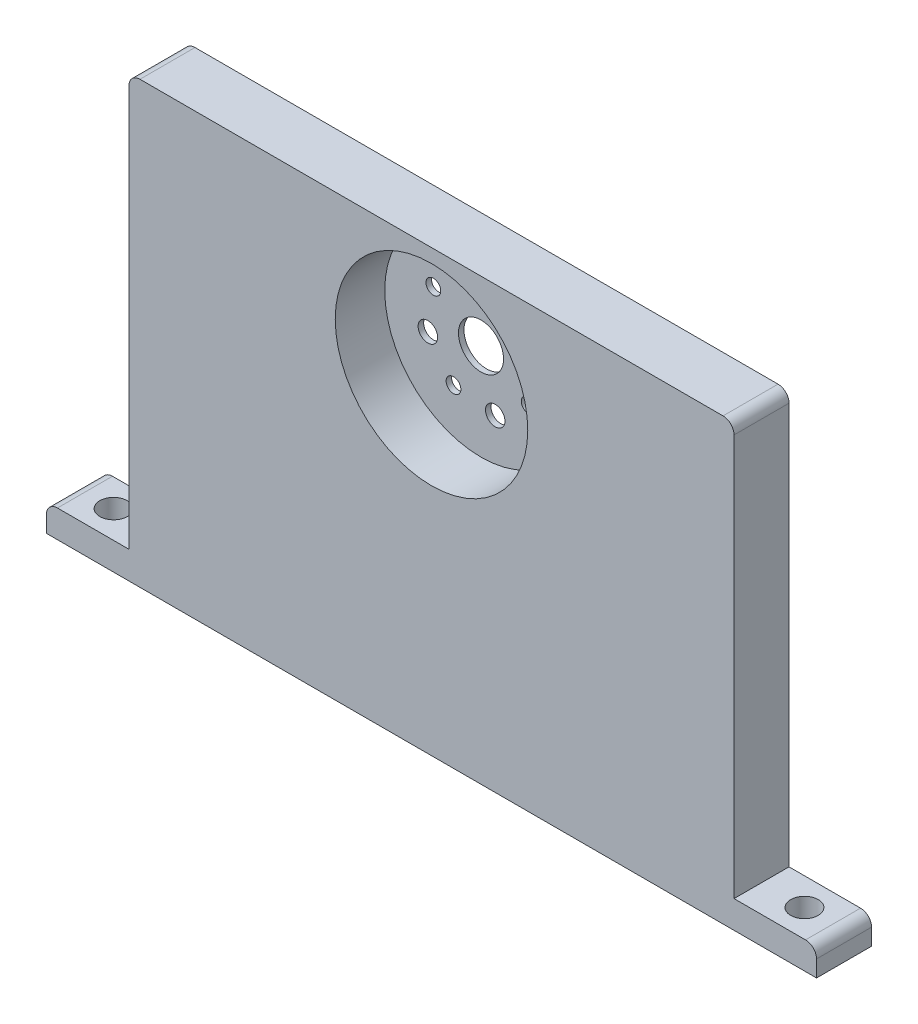
SolidWorks part; units mm, degrees
material "6061 Alloy"
ref_plane "Front Plane" through (0, 0, 0) normal (0, 0, 1) x (1, 0, 0)
ref_plane "Top Plane" through (0, 0, 0) normal (0, 1, 0) x (1, 0, 0)
ref_plane "Right Plane" through (0, 0, 0) normal (1, 0, 0) x (0, 0, -1)
sketch "Sketch1" plane through (0, 0, 0) normal (0, 1, 0) x (1, 0, 0)
  line L1 (0, 0) -> (139.7, 0)
  line L2 (0, 0) -> (0, 12.7)
  line L3 (0, 12.7) -> (139.7, 12.7)
  line L4 (139.7, 0) -> (139.7, 12.7)
  dimension "D1" = 12.7
  dimension "D2" = 139.7
extrude "Boss-Extrude1" add sketch "Sketch1" along normal blind 101.6
sketch "Sketch2" plane through (0, 0, 0) normal (-1, 0, 0) x (0, 0, 1)
  line L0 (-12.7, 101.6) -> (-12.7, 0) construction
  line L1 (0, 0) -> (-12.7, 0)
  line L2 (0, 0) -> (0, 6.35)
  line L3 (0, 6.35) -> (-12.7, 6.35)
  line L4 (-12.7, 0) -> (-12.7, 6.35)
  dimension "D1" = 6.35
extrude "Boss-Extrude2" add sketch "Sketch2" along normal blind 19.05
ref_plane "Plane1" through (69.85, 0, 0) normal (-1, 0, 0) x (0, 0, 1)
mirror "Mirror1" about plane through (69.85, 0, 0) normal (-1, 0, 0) of "Boss-Extrude2"
sketch "Sketch3" plane through (0, 0, 0) normal (0, 0, 1) x (1, 0, 0)
  line L0 (69.85, 101.6) -> (69.85, 0) construction
  line L1 (0, 101.6) -> (139.7, 101.6) construction
  line L2 (-19.05, 0) -> (158.75, 0) construction
  circle A0 centre (69.85, 76.2) radius 5.207
  dimension "D2" = 10.414
  dimension "D1" = 76.2
extrude "Cut-Extrude1" cut sketch "Sketch3" against normal up to next
sketch "Sketch4" plane through (0, 0, 0) normal (0, 0, 1) x (1, 0, 0)
  circle A0 centre (69.85, 76.2) radius 22.225
  dimension "D1" = 44.45
extrude "Cut-Extrude2" cut sketch "Sketch4" against normal blind 11.43
sketch "Sketch5" plane through (0, 0, -11.43) normal (0, 0, 1) x (1, 0, 0)
  line L0 (69.85, 76.2) -> (69.85, 88.9) construction
  line L1 (69.85, 76.2) -> (58.8515, 82.55) construction
  line L2 (69.85, 76.2) -> (66.563, 88.4673) construction
  line L3 (69.85, 76.2) -> (76.2, 87.1985) construction
  line L4 (69.85, 76.2) -> (82.1173, 79.487) construction
  line L5 (69.85, 76.2) -> (80.8485, 69.85) construction
  line L6 (69.85, 76.2) -> (73.137, 63.9327) construction
  line L7 (69.85, 76.2) -> (63.5, 65.2015) construction
  line L8 (69.85, 76.2) -> (57.5827, 72.913) construction
  circle A0 centre (69.85, 76.2) radius 12.7 construction
  circle A1 centre (58.8515, 82.55) radius 1.7018
  circle A2 centre (66.563, 88.4673) radius 2.2479
  circle A3 centre (82.1173, 79.487) radius 2.2479
  circle A4 centre (73.137, 63.9327) radius 2.2479
  circle A5 centre (57.5827, 72.913) radius 2.2479
  circle A6 centre (76.2, 87.1985) radius 1.7018
  circle A7 centre (80.8485, 69.85) radius 1.7018
  circle A8 centre (63.5, 65.2015) radius 1.7018
  point P6 (58.8515, 82.55)
  point P15 (69.85, 76.2)
  point P25 (69.85, 76.2)
  point P31 (69.85, 76.2)
  dimension "D1" = 25.4
  dimension "D4" = 3.4036
  dimension "D5" = 4.4958
  dimension "D2" = 60
  dimension "D3" = 8
  dimension "D6" = 4
  dimension "D7" = 4
extrude "Cut-Extrude3" cut sketch "Sketch5" against normal up to next
sketch "Sketch6" plane through (0, 6.35, 0) normal (0, 1, 0) x (1, 0, 0)
  line L0 (0, 0) -> (0, 12.7) construction
  line L3 (0, 6.35) -> (-19.05, 6.35) construction
  line L4 (-19.05, 0) -> (-19.05, 12.7) construction
  circle A0 centre (-9.906, 6.35) radius 3.175
  dimension "D1" = 6.35
  dimension "D2" = 9.906
extrude "Cut-Extrude4" cut sketch "Sketch6" against normal up to next
mirror "Mirror2" about plane through (69.85, 0, 0) normal (-1, 0, 0) of "Cut-Extrude4"
fillet "Fillet1" radius 2.54 4 edges at (158.75, 6.35, -6.35) (-19.05, 6.35, -6.35) (139.7, 101.6, -6.35) (0, 101.6, -6.35)
